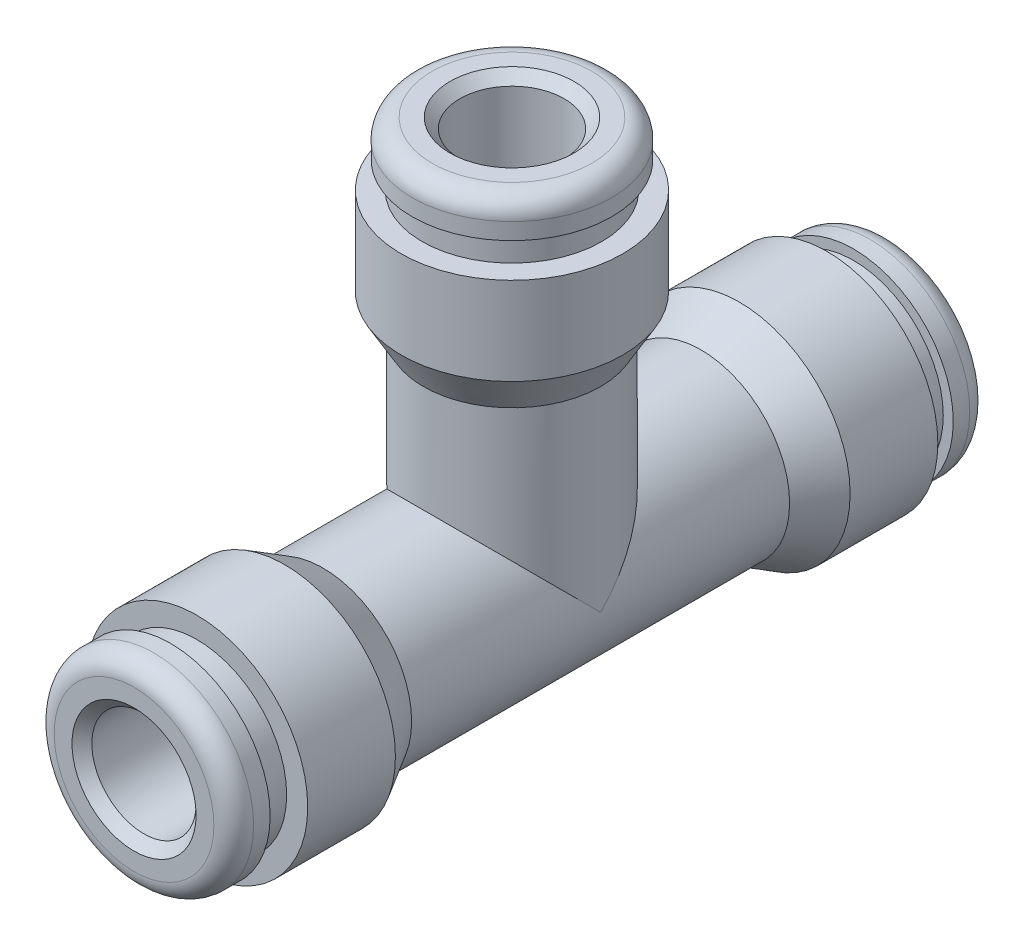
SolidWorks part; units mm, degrees
ref_plane "Front Plane" through (0, 0, 0) normal (0, 0, 1) x (1, 0, 0)
ref_plane "Top Plane" through (0, 0, 0) normal (0, 1, 0) x (1, 0, 0)
ref_plane "Right Plane" through (0, 0, 0) normal (1, 0, 0) x (0, 0, -1)
sketch "Sketch1" plane through (0, 0, 0) normal (1, 0, 0) x (0, 0, -1)
  line L0 (13.103, 3.825) -> (13.738, 3.825)
  line L1 (8.7222, 4.25) -> (12.087, 4.25)
  line L2 (0, 3.4) -> (0, 1.238)
  line L3 (4.35, 2) -> (14.119, 2)
  line L4 (14.5, 3.063) -> (14.5, 2.381)
  line L5 (0, 0) -> (0, 14.75) construction
  line L6 (12.087, 4.25) -> (12.087, 3.4425)
  line L7 (12.087, 3.4425) -> (13.103, 3.4425)
  line L8 (13.103, 3.825) -> (13.103, 3.4425)
  line L9 (-4.25, 14.75) -> (4.25, 14.75) construction
  line L10 (0, 0) -> (14.5, 0) construction
  line L11 (4.35, 2) -> (4.35, 1.238)
  line L12 (14.119, 2) -> (14.5, 2.381)
  line L13 (0, 0) -> (0, 1.238) construction
  line L14 (0, 3.4) -> (7.25, 3.4)
  line L15 (7.25, 3.4) -> (8.7222, 4.25)
  line L16 (4.35, 1.238) -> (0, 1.238)
  line L17 (0, 14.5) -> (0, 0) construction
  line L22 (0, 0) -> (-14.5, 0) construction
  arc A0 (13.738, 3.825) -> (14.5, 3.063) centre (13.738, 3.063) cw
  point P1 (14.5, 2)
  point P2 (14.5, 4.25)
  point P17 (14.5, -4.25)
  point P20 (14.5, 3.825)
  point P26 (-14.5, -4.25)
  dimension "D4" = 0.762
  dimension "tube od" = 4
  dimension "D1" = 1.397
  dimension "D2" = 1.016
  dimension "D3" = 6.885
  dimension "D6" = 7.65
  dimension "D9" = 30
  dimension "D10" = 6.8
  dimension "D5" = 7.25
  dimension "D8" = 8.5
  dimension "D11" = 0.762
revolve "Revolve1" add sketch "Sketch1" angle 360 about L10
ref_axis "Axis1" through (-6.05, 0, 0) along (1, 0, 0)
pattern_circular "CirPattern1" count 3 over 180 about axis through (0, 0, 0) along (1, 0, 0) of bodies 118 123
move or copy body "Body-Move/Copy1" bodies to move or copy 124 copy no translate (0, 0.25, 0)
sketch "Sketch3" plane through (0, 0, 0) normal (0, 1, 0) x (1, 0, 0)
  circle A0 centre (0, 0) radius 3.4 construction
  circle A1 centre (0, 0) radius 3.4
extrude "Boss-Extrude1" add sketch "Sketch3" along normal up to surface (0.25 mm away) up to face at (1.238, 0.25, 0)
sketch "Sketch4" plane through (0, 0, 0) normal (1, 0, 0) x (0, 0, -1)
  line L0 (2, 14.369) -> (2.381, 14.75)
  line L1 (2.381, 14.75) -> (0, 14.75)
  line L2 (0, 14.75) -> (0, 0)
  line L4 (1.238, 0) -> (1.238, 4.6)
  line L5 (1.238, 4.6) -> (2, 4.6)
  line L6 (2, 4.6) -> (2, 14.369)
  line L7 (1.238, 0) -> (0, 0)
  line L9 (1.238, 4.6) -> (-1.238, 4.6) construction
  line L10 (2, 4.6) -> (-2, 4.6) construction
revolve "Cut-Revolve2" cut sketch "Sketch4" angle 360 about L5
combine bodies "Combine1" operation type add bodies to combine 145 149 146
sketch "Sketch5" plane through (0, 0, 0) normal (1, 0, 0) x (0, 0, -1)
  line L0 (14.5, 2.381) -> (14.119, 2)
  line L1 (14.119, 2) -> (4.35, 2)
  line L2 (4.35, 2) -> (4.35, 1.238)
  line L3 (4.35, 1.238) -> (0, 1.238)
  line L4 (0, 1.238) -> (0, 0)
  line L5 (0, 0) -> (14.5, 0)
  line L6 (14.5, 0) -> (14.5, 2.381)
revolve "Cut-Revolve1" cut sketch "Sketch5" angle 360 about L5
pattern_circular "CirPattern2" count 2 over 180 about axis through (-6.05, 0, 0) along (1, 0, 0) of "Cut-Revolve1"
equation "\"D6@Sketch1\" = \"G@Sketch1\"*.9"
equation "\"D3@Sketch1\" = \"D6@Sketch1\"*.9"
equation "\"D10@Sketch1\" = \"G@Sketch1\"*.8"
equation "\"D5@Sketch1\" = \"L/2@Sketch1\"*.5"
equation "\"D8@Sketch1\" = \"G@Sketch1\""
